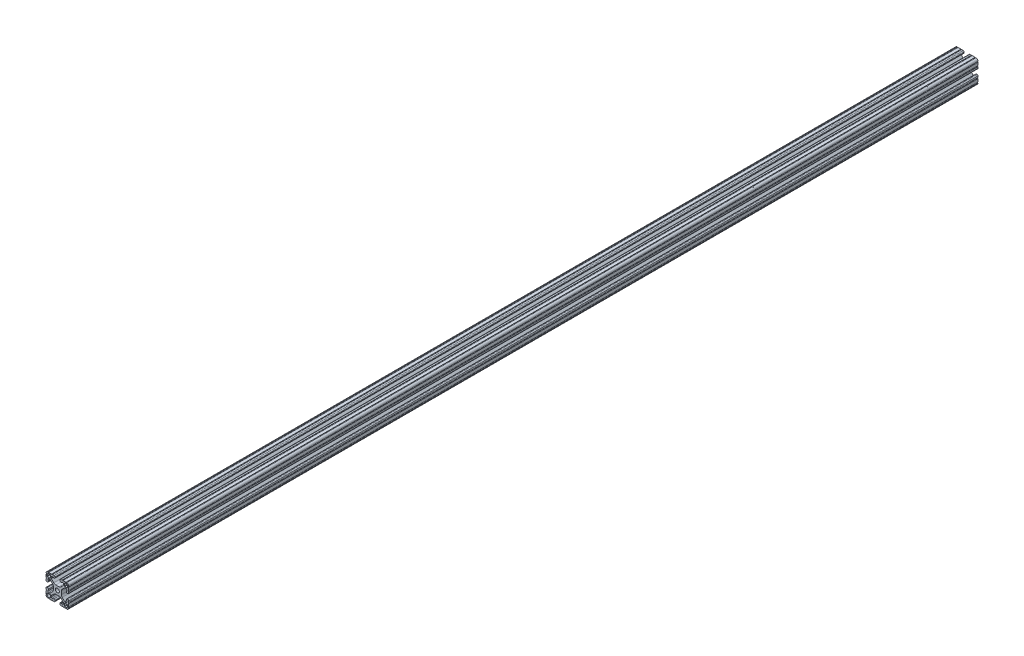
SolidWorks part; units mm, degrees
material "6061 Alloy"
ref_plane "Front Plane" through (0, 0, 0) normal (0, 0, 1) x (1, 0, 0)
ref_plane "Top Plane" through (0, 0, 0) normal (0, 1, 0) x (1, 0, 0)
ref_plane "Right Plane" through (0, 0, 0) normal (1, 0, 0) x (0, 0, -1)
sketch "Sketch1" plane through (0, 0, 0) normal (0, 0, 1) x (1, 0, 0)
  line L0 (0, 21.507) -> (0, -20.9529) construction
  line L1 (20.4424, 0) -> (-20.8151, 0) construction
  line L2 (10.0267, -12.1519) -> (6.0215, -8.1473)
  line L3 (-10.0267, 12.1519) -> (-6.0215, 8.1473)
  line L4 (-10.287, 14.5547) -> (-10.287, 12.7802)
  line L5 (-6.8141, 15.8247) -> (-9.017, 15.8247)
  line L6 (10.287, -14.5547) -> (10.287, -12.7802)
  line L7 (-6.8141, 14.986) -> (-6.8141, 15.8247)
  line L8 (6.8141, -15.8247) -> (9.017, -15.8247)
  line L9 (-2.6631, -6.7564) -> (2.6631, -6.7564)
  line L10 (6.8141, -14.986) -> (6.8141, -15.8247)
  line L11 (5.6388, -14.986) -> (6.8141, -14.986)
  line L12 (4.064, -17.4752) -> (4.064, -16.5608)
  line L13 (7.9756, -19.05) -> (5.6388, -19.05)
  line L14 (14.3256, -19.05) -> (9.4996, -19.05)
  line L15 (15.875, -19.05) -> (15.8496, -19.05)
  line L16 (19.05, -15.8496) -> (19.05, -15.875)
  line L17 (19.05, -9.4996) -> (19.05, -14.3256)
  line L18 (19.05, -5.6388) -> (19.05, -7.9756)
  line L19 (-5.6388, 14.986) -> (-6.8141, 14.986)
  line L20 (-4.064, 17.4752) -> (-4.064, 16.5608)
  line L21 (-7.9756, 19.05) -> (-5.6388, 19.05)
  line L22 (16.5608, -4.064) -> (17.4752, -4.064)
  line L23 (-14.3256, 19.05) -> (-9.4996, 19.05)
  line L24 (14.986, -6.7506) -> (14.986, -5.6388)
  line L25 (15.879, -6.7506) -> (14.986, -6.7506)
  line L26 (-15.875, 19.05) -> (-15.8496, 19.05)
  line L27 (-19.05, 15.8496) -> (-19.05, 15.875)
  line L28 (15.879, -8.9192) -> (15.879, -6.7506)
  line L29 (12.7428, -10.1892) -> (14.609, -10.1892)
  line L30 (-19.05, 9.4996) -> (-19.05, 14.3256)
  line L31 (-19.05, 5.6388) -> (-19.05, 7.9756)
  line L32 (8.1479, -5.9632) -> (12.1142, -9.9289)
  line L33 (16.891, -11.8618) -> (12.2428, -11.8618)
  line L34 (11.8618, -12.2428) -> (11.8618, -16.891)
  line L35 (12.2428, -17.272) -> (14.478, -17.272)
  line L36 (17.272, 14.478) -> (17.272, 12.2428)
  line L37 (12.2428, 17.272) -> (14.478, 17.272)
  line L38 (11.8618, 12.2428) -> (11.8618, 16.891)
  line L39 (16.891, 11.8618) -> (12.2428, 11.8618)
  line L40 (17.272, -14.478) -> (17.272, -12.2428)
  line L41 (-16.5608, 4.064) -> (-17.4752, 4.064)
  line L42 (-14.986, 6.7506) -> (-14.986, 5.6388)
  line L43 (-15.879, 6.7506) -> (-14.986, 6.7506)
  line L44 (-15.879, 8.9192) -> (-15.879, 6.7506)
  line L45 (-12.7428, 10.1892) -> (-14.609, 10.1892)
  line L46 (-8.1479, 5.9632) -> (-12.1142, 9.9289)
  line L47 (-6.7564, -2.6043) -> (-6.7564, 2.6043)
  line L48 (-17.272, -14.478) -> (-17.272, -12.2428)
  line L49 (-16.891, 11.8618) -> (-12.2428, 11.8618)
  line L50 (-11.8618, 12.2428) -> (-11.8618, 16.891)
  line L51 (-12.2428, 17.272) -> (-14.478, 17.272)
  line L52 (-17.272, 14.478) -> (-17.272, 12.2428)
  line L53 (-12.2428, -17.272) -> (-14.478, -17.272)
  line L54 (-11.8618, -12.2428) -> (-11.8618, -16.891)
  line L55 (-16.891, -11.8618) -> (-12.2428, -11.8618)
  line L56 (-8.1479, -5.9632) -> (-12.1142, -9.9289)
  line L57 (-12.7428, -10.1892) -> (-14.609, -10.1892)
  line L58 (-15.879, -8.9192) -> (-15.879, -6.7506)
  line L59 (-15.879, -6.7506) -> (-14.986, -6.7506)
  line L60 (-14.986, -6.7506) -> (-14.986, -5.6388)
  line L61 (-16.5608, -4.064) -> (-17.4752, -4.064)
  line L62 (-19.05, -5.6388) -> (-19.05, -7.9756)
  line L63 (-19.05, -9.4996) -> (-19.05, -14.3256)
  line L64 (-19.05, -15.8496) -> (-19.05, -15.875)
  line L65 (-15.875, -19.05) -> (-15.8496, -19.05)
  line L66 (-14.3256, -19.05) -> (-9.4996, -19.05)
  line L67 (-7.9756, -19.05) -> (-5.6388, -19.05)
  line L68 (-4.064, -17.4752) -> (-4.064, -16.5608)
  line L69 (-5.6388, -14.986) -> (-6.8141, -14.986)
  line L70 (-6.8141, -14.986) -> (-6.8141, -15.8247)
  line L71 (-6.8141, -15.8247) -> (-9.017, -15.8247)
  line L72 (-10.287, -14.5547) -> (-10.287, -12.7802)
  line L73 (-10.0267, -12.1519) -> (-6.0215, -8.1473)
  line L95 (6.7564, -2.6043) -> (6.7564, 2.6043)
  line L96 (8.1479, 5.9632) -> (12.1142, 9.9289)
  line L97 (12.7428, 10.1892) -> (14.609, 10.1892)
  line L98 (15.879, 8.9192) -> (15.879, 6.7506)
  line L99 (15.879, 6.7506) -> (14.986, 6.7506)
  line L100 (14.986, 6.7506) -> (14.986, 5.6388)
  line L101 (16.5608, 4.064) -> (17.4752, 4.064)
  line L102 (19.05, 5.6388) -> (19.05, 7.9756)
  line L103 (19.05, 9.4996) -> (19.05, 14.3256)
  line L104 (19.05, 15.8496) -> (19.05, 15.875)
  line L105 (15.875, 19.05) -> (15.8496, 19.05)
  line L106 (14.3256, 19.05) -> (9.4996, 19.05)
  line L107 (7.9756, 19.05) -> (5.6388, 19.05)
  line L108 (4.064, 17.4752) -> (4.064, 16.5608)
  line L109 (5.6388, 14.986) -> (6.8141, 14.986)
  line L110 (6.8141, 14.986) -> (6.8141, 15.8247)
  line L111 (6.8141, 15.8247) -> (9.017, 15.8247)
  line L112 (10.287, 14.5547) -> (10.287, 12.7802)
  line L113 (10.0267, 12.1519) -> (6.0215, 8.1473)
  line L114 (2.6631, 6.7564) -> (-2.6631, 6.7564)
  arc A0 (10.0267, -12.1519) -> (10.287, -12.7802) centre (9.3985, -12.7802) cw
  arc A1 (10.287, -14.5547) -> (9.017, -15.8247) centre (9.017, -14.5547) cw
  arc A2 (4.064, -16.5608) -> (5.6388, -14.986) centre (5.6388, -16.5608) cw
  arc A3 (-10.0267, 12.1519) -> (-10.287, 12.7802) centre (-9.3985, 12.7802) cw
  arc A4 (-10.287, 14.5547) -> (-9.017, 15.8247) centre (-9.017, 14.5547) cw
  arc A5 (5.6388, -19.05) -> (4.064, -17.4752) centre (5.6388, -17.4752) cw
  arc A6 (7.9756, -19.05) -> (9.4996, -19.05) centre (8.7376, -19.05) cw
  arc A7 (-4.064, 16.5608) -> (-5.6388, 14.986) centre (-5.6388, 16.5608) cw
  arc A8 (14.3256, -19.05) -> (15.8496, -19.05) centre (15.0876, -19.05) cw
  arc A9 (19.05, -15.875) -> (15.875, -19.05) centre (15.875, -15.875) cw
  arc A10 (6.0215, -8.1473) -> (2.6631, -6.7564) centre (2.6631, -11.5062) ccw
  arc A11 (-6.0215, -8.1473) -> (-2.6631, -6.7564) centre (-2.6631, -11.5062) cw
  arc A12 (19.05, -15.8496) -> (19.05, -14.3256) centre (19.05, -15.0876) cw
  arc A13 (19.05, -9.4996) -> (19.05, -7.9756) centre (19.05, -8.7376) cw
  arc A14 (17.4752, -4.064) -> (19.05, -5.6388) centre (17.4752, -5.6388) cw
  arc A15 (14.986, -5.6388) -> (16.5608, -4.064) centre (16.5608, -5.6388) cw
  arc A16 (15.879, -8.9192) -> (14.609, -10.1892) centre (14.609, -8.9192) cw
  arc A17 (12.7428, -10.1892) -> (12.1142, -9.9289) centre (12.7428, -9.3002) cw
  arc A18 (16.891, -11.8618) -> (17.272, -12.2428) centre (16.891, -12.2428) cw
  arc A19 (-5.6388, 19.05) -> (-4.064, 17.4752) centre (-5.6388, 17.4752) cw
  arc A20 (-7.9756, 19.05) -> (-9.4996, 19.05) centre (-8.7376, 19.05) cw
  arc A21 (-14.3256, 19.05) -> (-15.8496, 19.05) centre (-15.0876, 19.05) cw
  arc A22 (11.8618, -12.2428) -> (12.2428, -11.8618) centre (12.2428, -12.2428) cw
  arc A23 (-19.05, 15.875) -> (-15.875, 19.05) centre (-15.875, 15.875) cw
  arc A24 (12.2428, -17.272) -> (11.8618, -16.891) centre (12.2428, -16.891) cw
  arc A25 (17.272, -14.478) -> (14.478, -17.272) centre (14.478, -14.478) cw
  arc A26 (-19.05, 15.8496) -> (-19.05, 14.3256) centre (-19.05, 15.0876) cw
  arc A27 (-19.05, 9.4996) -> (-19.05, 7.9756) centre (-19.05, 8.7376) cw
  arc A28 (-17.4752, 4.064) -> (-19.05, 5.6388) centre (-17.4752, 5.6388) cw
  arc A29 (-14.986, 5.6388) -> (-16.5608, 4.064) centre (-16.5608, 5.6388) cw
  arc A30 (-15.879, 8.9192) -> (-14.609, 10.1892) centre (-14.609, 8.9192) cw
  arc A31 (-12.7428, 10.1892) -> (-12.1142, 9.9289) centre (-12.7428, 9.3002) cw
  arc A32 (-8.1479, 5.9632) -> (-6.7564, 2.6043) centre (-11.5062, 2.6043) cw
  arc A33 (-6.7564, -2.6043) -> (-8.1479, -5.9632) centre (-11.5062, -2.6043) cw
  arc A34 (-16.891, 11.8618) -> (-17.272, 12.2428) centre (-16.891, 12.2428) cw
  arc A35 (-11.8618, 12.2428) -> (-12.2428, 11.8618) centre (-12.2428, 12.2428) cw
  arc A36 (17.272, 14.478) -> (14.478, 17.272) centre (14.478, 14.478) ccw
  arc A37 (12.2428, 17.272) -> (11.8618, 16.891) centre (12.2428, 16.891) ccw
  arc A38 (11.8618, 12.2428) -> (12.2428, 11.8618) centre (12.2428, 12.2428) ccw
  arc A39 (16.891, 11.8618) -> (17.272, 12.2428) centre (16.891, 12.2428) ccw
  arc A40 (-12.2428, 17.272) -> (-11.8618, 16.891) centre (-12.2428, 16.891) cw
  circle A41 centre (0, 0) radius 3.3274
  arc A42 (-17.272, 14.478) -> (-14.478, 17.272) centre (-14.478, 14.478) cw
  arc A43 (-17.272, -14.478) -> (-14.478, -17.272) centre (-14.478, -14.478) ccw
  arc A44 (-12.2428, -17.272) -> (-11.8618, -16.891) centre (-12.2428, -16.891) ccw
  arc A45 (-11.8618, -12.2428) -> (-12.2428, -11.8618) centre (-12.2428, -12.2428) ccw
  arc A46 (-16.891, -11.8618) -> (-17.272, -12.2428) centre (-16.891, -12.2428) ccw
  arc A47 (-12.7428, -10.1892) -> (-12.1142, -9.9289) centre (-12.7428, -9.3002) ccw
  arc A48 (-15.879, -8.9192) -> (-14.609, -10.1892) centre (-14.609, -8.9192) ccw
  arc A49 (-14.986, -5.6388) -> (-16.5608, -4.064) centre (-16.5608, -5.6388) ccw
  arc A50 (-17.4752, -4.064) -> (-19.05, -5.6388) centre (-17.4752, -5.6388) ccw
  arc A51 (-19.05, -9.4996) -> (-19.05, -7.9756) centre (-19.05, -8.7376) ccw
  arc A52 (-19.05, -15.8496) -> (-19.05, -14.3256) centre (-19.05, -15.0876) ccw
  arc A53 (-19.05, -15.875) -> (-15.875, -19.05) centre (-15.875, -15.875) ccw
  arc A54 (-14.3256, -19.05) -> (-15.8496, -19.05) centre (-15.0876, -19.05) ccw
  arc A55 (-7.9756, -19.05) -> (-9.4996, -19.05) centre (-8.7376, -19.05) ccw
  arc A56 (-5.6388, -19.05) -> (-4.064, -17.4752) centre (-5.6388, -17.4752) ccw
  arc A57 (-4.064, -16.5608) -> (-5.6388, -14.986) centre (-5.6388, -16.5608) ccw
  arc A58 (-10.287, -14.5547) -> (-9.017, -15.8247) centre (-9.017, -14.5547) ccw
  arc A59 (-10.0267, -12.1519) -> (-10.287, -12.7802) centre (-9.3985, -12.7802) ccw
  arc A86 (6.7564, -2.6043) -> (8.1479, -5.9632) centre (11.5062, -2.6043) ccw
  arc A87 (8.1479, 5.9632) -> (6.7564, 2.6043) centre (11.5062, 2.6043) ccw
  arc A88 (12.7428, 10.1892) -> (12.1142, 9.9289) centre (12.7428, 9.3002) ccw
  arc A89 (15.879, 8.9192) -> (14.609, 10.1892) centre (14.609, 8.9192) ccw
  arc A90 (14.986, 5.6388) -> (16.5608, 4.064) centre (16.5608, 5.6388) ccw
  arc A91 (17.4752, 4.064) -> (19.05, 5.6388) centre (17.4752, 5.6388) ccw
  arc A92 (19.05, 9.4996) -> (19.05, 7.9756) centre (19.05, 8.7376) ccw
  arc A93 (19.05, 15.8496) -> (19.05, 14.3256) centre (19.05, 15.0876) ccw
  arc A94 (19.05, 15.875) -> (15.875, 19.05) centre (15.875, 15.875) ccw
  arc A95 (14.3256, 19.05) -> (15.8496, 19.05) centre (15.0876, 19.05) ccw
  arc A96 (7.9756, 19.05) -> (9.4996, 19.05) centre (8.7376, 19.05) ccw
  arc A97 (5.6388, 19.05) -> (4.064, 17.4752) centre (5.6388, 17.4752) ccw
  arc A98 (4.064, 16.5608) -> (5.6388, 14.986) centre (5.6388, 16.5608) ccw
  arc A99 (10.287, 14.5547) -> (9.017, 15.8247) centre (9.017, 14.5547) ccw
  arc A100 (10.0267, 12.1519) -> (10.287, 12.7802) centre (9.3985, 12.7802) ccw
  arc A101 (2.6631, 6.7564) -> (6.0215, 8.1473) centre (2.6631, 11.5062) ccw
  arc A102 (-6.0215, 8.1473) -> (-2.6631, 6.7564) centre (-2.6631, 11.5062) ccw
  dimension "D1" = 6.6548
  dimension "D2" = 38.1
  dimension "D3" = 20.574
  dimension "D4" = 12.2936
  dimension "D5" = 19.05
  dimension "D6" = 8.128
  dimension "D7" = 3.048
  dimension "D8" = 4.064
  dimension "D9" = 13.5128
extrude "Extrude1" add sketch "Sketch1" against normal blind 1524
